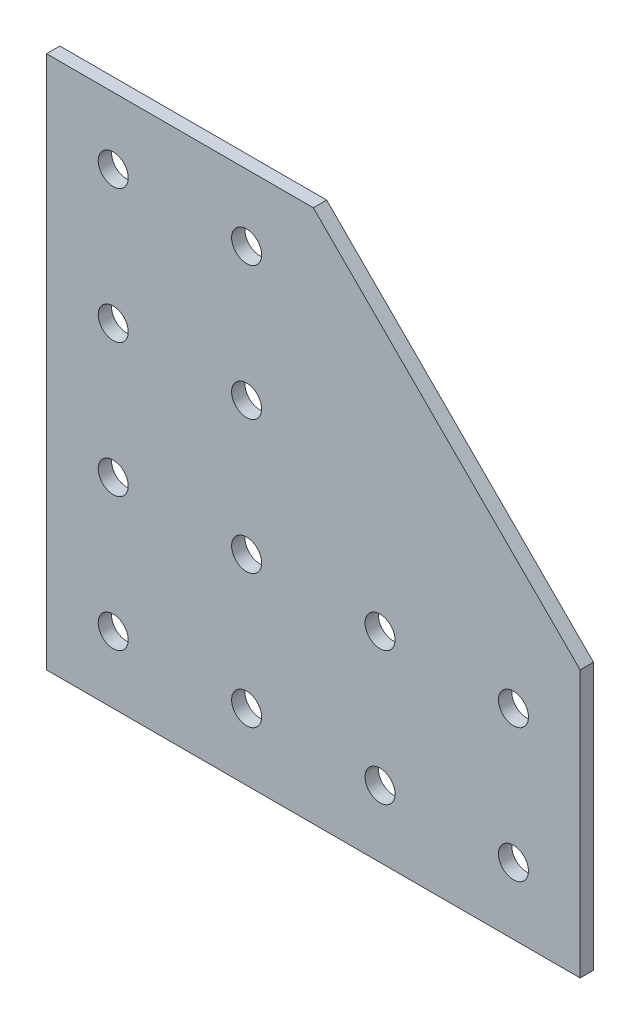
SolidWorks part; units mm, degrees
material "Простая углеродистая сталь"
ref_plane "Спереди" through (0, 0, 0) normal (0, 0, 1) x (1, 0, 0)
ref_plane "Сверху" through (0, 0, 0) normal (0, 1, 0) x (1, 0, 0)
ref_plane "Справа" through (0, 0, 0) normal (1, 0, 0) x (0, 0, -1)
sketch "Эскиз1" plane through (0, 0, 0) normal (0, 0, 1) x (1, 0, 0)
  line L0 (0, 0) -> (0, 80)
  line L1 (0, 80) -> (40, 80)
  line L2 (40, 80) -> (80, 40)
  line L3 (80, 40) -> (80, 0)
  line L4 (80, 0) -> (0, 0)
  dimension "D1" = 40
  dimension "D2" = 80
  dimension "D3" = 80
extrude "Бобышка-Вытянуть1" add sketch "Эскиз1" along normal blind 2
hole_wizard "Отверстие с зазором M41" positions "Эскиз3" profile "Эскиз2" hole size "M4" standard "DIN"
sketch "Эскиз3" plane through (0, 0, 0) normal (0, 0, -1) x (-1, 0, 0)
  line L0 (0, 0) -> (-80, 0) construction
  line L1 (-80, 0) -> (-80, 40) construction
  line L2 (0, 80) -> (0, 0) construction
  line L3 (-40, 80) -> (0, 80) construction
  point P0 (-70, 10)
  point P9 (-30, 50)
  point P22 (-50, 10)
  point P23 (-10, 50)
  point P24 (-70, 30)
  point P25 (-30, 70)
  point P26 (-50, 30)
  point P27 (-10, 70)
  point P34 (-30, 10)
  point P35 (-10, 10)
  point P36 (-50, 30)
  point P37 (-30, 30)
  point P38 (-10, 30)
  dimension "D1" = 10
  dimension "D2" = 10
  dimension "D3" = 30
  dimension "D4" = 30
  dimension "D9" = 20
  dimension "D10" = 20
  dimension "D11" = 20
  dimension "D12" = 20
  dimension "D5" = 2
  dimension "D6" = 2
  dimension "D7" = 3
  dimension "D8" = 2
sketch "Эскиз2" plane through (70, 10, 0) normal (1, 0, 0) x (0, 1, 0)
  line L0 (0, 0) -> (0, 6.3519)
  line L1 (0, 6.3519) -> (2.25, 5)
  line L2 (2.25, 5) -> (2.25, 0)
  line L5 (2.25, 0) -> (0, 0)
  line L10 (0, 6.3519) -> (-2.25, 5) construction
  line L11 (0, -6.35) -> (0, 107.95) construction
  dimension "Диаметр отверстия" = 4.5
  dimension "Глубина отверстия" = 5
  dimension "Угол заточки сверла" = 118
